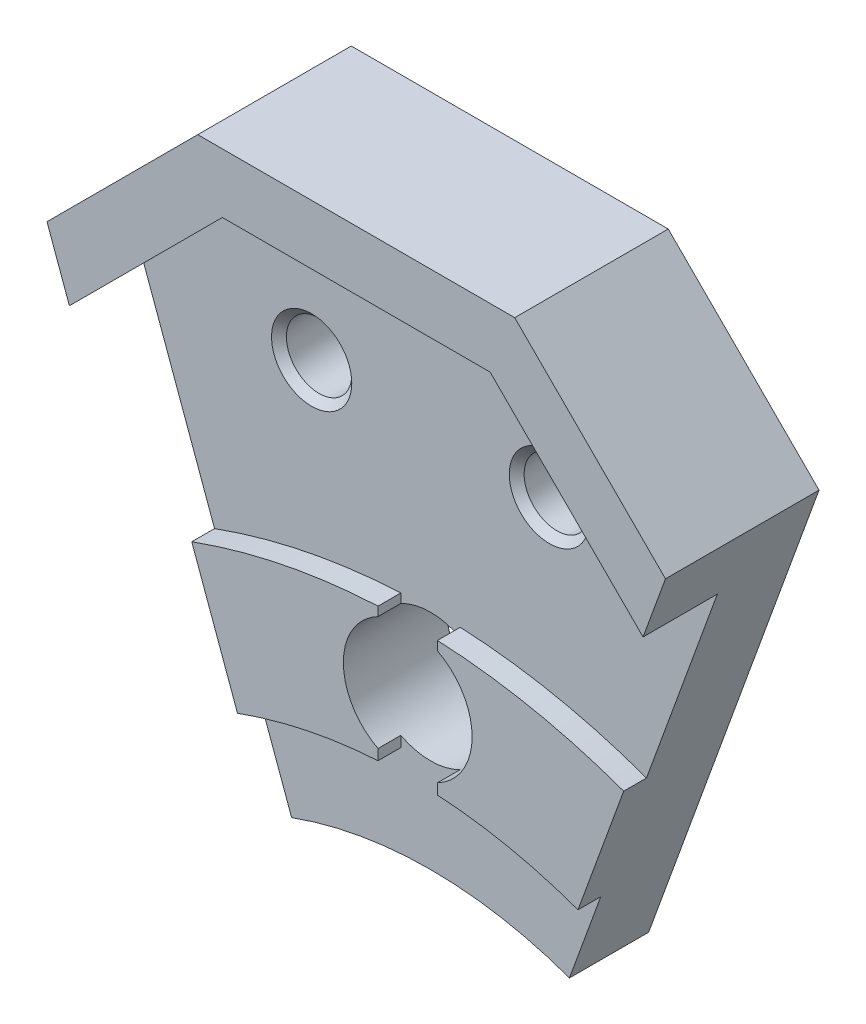
SolidWorks part; units mm, degrees
ref_plane "Front Plane" through (0, 0, 0) normal (0, 0, 1) x (1, 0, 0)
ref_plane "Top Plane" through (0, 0, 0) normal (0, 1, 0) x (1, 0, 0)
ref_plane "Right Plane" through (0, 0, 0) normal (1, 0, 0) x (0, 0, -1)
sketch "Esquisse2" plane through (0, 0, 0) normal (0, 0, 1) x (1, 0, 0)
  line L0 (0, 0) -> (0, 50.5) construction
  line L1 (-8, 50.5) -> (8, 50.5)
  line L2 (-8, 50.5) -> (-15.6105, 42.8895)
  line L3 (8, 50.5) -> (15.6105, 42.8895)
  line L4 (7.0114, 19.2637) -> (15.6105, 42.8895)
  line L5 (-7.0114, 19.2637) -> (-15.6105, 42.8895)
  arc A0 (7.0114, 19.2637) -> (-7.0114, 19.2637) centre (0, 0) ccw
  circle A2 centre (0, 28.5) radius 3.25
  dimension "D5" = 20.5
  dimension "D6" = 6.5
  dimension "D1" = 16
  dimension "D2" = 45
  dimension "D3" = 50.5
  dimension "D4" = 40
  dimension "D7" = 28.5
extrude "Boss.-Extru.3" add sketch "Esquisse2" along normal mid plane 4
sketch "Esquisse3" plane through (0, 0, 2) normal (0, 0, 1) x (1, 0, 0)
  line L0 (15.6105, 42.8895) -> (8, 50.5) construction
  line L1 (8, 50.5) -> (-8, 50.5) construction
  line L2 (-8, 50.5) -> (-15.6105, 42.8895) construction
  line L3 (15.6105, 42.8895) -> (8, 50.5)
  line L4 (8, 50.5) -> (-8, 50.5)
  line L5 (-8, 50.5) -> (-15.6105, 42.8895)
  line L6 (14.4784, 39.779) -> (6.7574, 47.5)
  line L7 (6.7574, 47.5) -> (-6.7574, 47.5)
  line L8 (-6.7574, 47.5) -> (-14.4784, 39.779)
  line L9 (-6.7574, 47.5) -> (-13.4892, 40.7682) construction
  line L10 (13.4892, 40.7682) -> (6.7574, 47.5) construction
  line L11 (7.0114, 19.2637) -> (15.6105, 42.8895) construction
  line L12 (-15.6105, 42.8895) -> (-7.0114, 19.2637) construction
  line L13 (14.4784, 39.779) -> (15.6105, 42.8895)
  line L14 (-15.6105, 42.8895) -> (-14.4784, 39.779)
  dimension "D1" = 3
extrude "Boss.-Extru.4" add sketch "Esquisse3" along normal mid plane 7.5
sketch "Esquisse4" plane through (0, 0, 2) normal (0, 0, 1) x (1, 0, 0)
  line L0 (7.0114, 19.2637) -> (14.4784, 39.779) construction
  line L1 (-14.4784, 39.779) -> (-7.0114, 19.2637) construction
  line L2 (8.5933, 23.6098) -> (10.9019, 29.9527)
  line L3 (-10.9019, 29.9527) -> (-8.5933, 23.6098)
  line L4 (0, 0) -> (0, 33.8384) construction
  line L6 (-1.5, 31.8397) -> (-1.5, 31.3831)
  line L8 (1.5, 31.8397) -> (1.5, 31.3831)
  line L9 (-1.5, 25.6169) -> (-1.5, 25.0802)
  line L10 (1.5, 25.6169) -> (1.5, 25.0802)
  arc A0 (-8.5933, 23.6098) -> (-1.5, 25.0802) centre (0, 0) cw
  arc A1 (-10.9019, 29.9527) -> (-1.5, 31.8397) centre (0, 0) cw
  circle A2 centre (0, 28.5) radius 3.25 construction
  arc A3 (-1.5, 31.3831) -> (-1.5, 25.6169) centre (0, 28.5) ccw
  arc A4 (1.5, 25.0802) -> (8.5933, 23.6098) centre (0, 0) cw
  arc A5 (1.5, 31.8397) -> (10.9019, 29.9527) centre (0, 0) cw
  arc A6 (1.5, 25.6169) -> (1.5, 31.3831) centre (0, 28.5) ccw
  dimension "D1" = 25.125
  dimension "D2" = 31.875
extrude "Boss.-Extru.5" add sketch "Esquisse4" along normal mid plane 2.3
hole_wizard "Trou taraudé M43" positions "Esquisse11" profile "Esquisse12" tap size "M4" standard "ISO" end condition through all
sketch "Esquisse11" plane through (0, 0, 2) normal (0, 0, 1) x (1, 0, 0)
  line L0 (0, 0) -> (0, 53.9288) construction
  line L2 (-6, 39.7721) -> (6, 39.7721) construction
  line L3 (-6.7574, 47.5) -> (-14.4784, 39.779) construction
  point P0 (-6, 39.7721)
  point P2 (6, 39.7721)
  dimension "D1" = 12
  dimension "D2" = 6
sketch "Esquisse12" plane through (-6, 39.7721, 2) normal (1, 0, 0) x (0, -1, 0)
  line L0 (0, 0) -> (0, 4)
  line L1 (0, 4) -> (1.65, 4)
  line L2 (1.65, 4) -> (1.65, 0.375)
  line L3 (1.65, 0.375) -> (2.025, 0)
  line L5 (2.025, 0) -> (0, 0)
  line L6 (-1.65, 0.375) -> (-2.025, 0) construction
  line L11 (0, -6.35) -> (0, 107.95) construction
  dimension "Diamètre du trou pour taraudage jusqu'au prochain" = 3.3
  dimension "Profondeur du trou pour taraudage jusqu'au prochain" = 4
  dimension "Diamètre du fraisage entrant" = 4.05
  dimension "Angle du fraisage entrant" = 90
cosmetic thread "Filetage de perçage6" parameters "D2"=4
cosmetic thread "Filetage de perçage7" parameters "D2"=4
